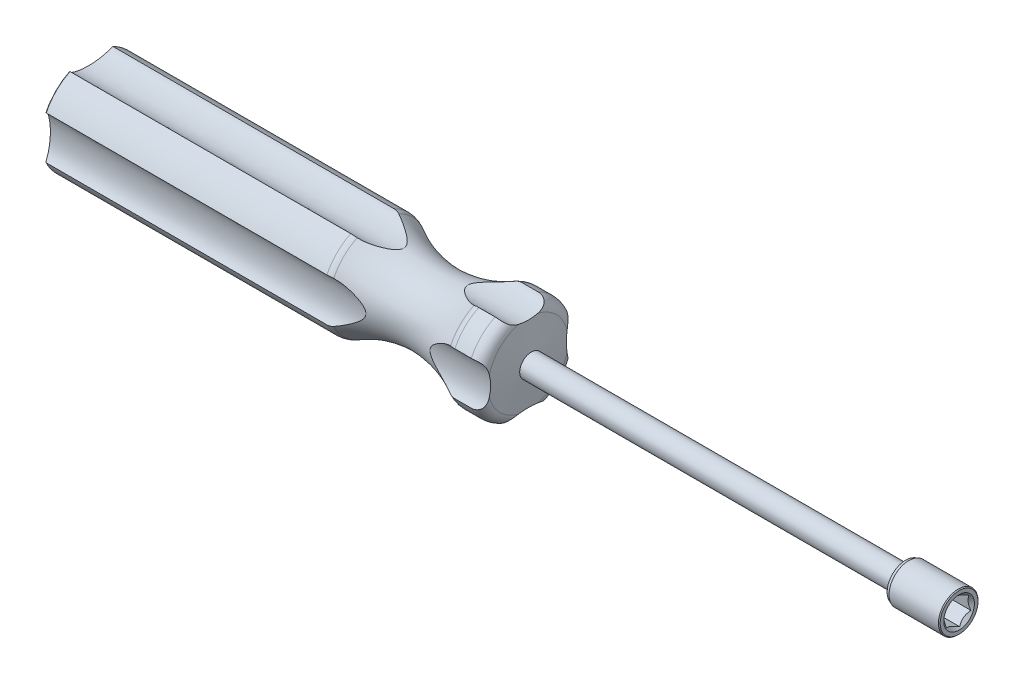
SolidWorks part; units mm, degrees
ref_plane "Front Plane" through (0, 0, 0) normal (0, 0, 1) x (1, 0, 0)
ref_plane "Top Plane" through (0, 0, 0) normal (0, 1, 0) x (1, 0, 0)
ref_plane "Right Plane" through (0, 0, 0) normal (1, 0, 0) x (0, 0, -1)
sketch "Sketch1" plane through (0, 0, 0) normal (0, 0, 1) x (1, 0, 0)
  line L0 (0, 0) -> (113.716, 0)
  line L1 (0, 4) -> (113.716, 4)
  line L4 (121.1868, 0) -> (113.716, 0)
  line L5 (113.716, 4) -> (114.9014, 6.8393)
  line L6 (0, 4) -> (-66.9286, 4)
  line L7 (114.9014, 6.8393) -> (133.21, 6.8393)
  line L8 (0, 0) -> (-66.9286, 0)
  line L9 (-66.9286, 4) -> (-66.9286, 0)
  line L10 (133.21, 6.8393) -> (133.21, 0)
  line L11 (133.21, 0) -> (121.1868, 0)
  dimension "D1" = 4
revolve "Revolve1" add sketch "Sketch1" angle 360 about L8
sketch "Sketch6" plane through (133.21, 0, 0) normal (1, 0, 0) x (0, 0, -1)
  line L1 (3.8609, 2.9631) -> (-0.6356, 4.8252)
  line L2 (-0.6356, 4.8252) -> (-4.4966, 1.8621)
  line L3 (-4.4966, 1.8621) -> (-3.8609, -2.9631)
  line L4 (-3.8609, -2.9631) -> (0.6356, -4.8252)
  line L5 (0.6356, -4.8252) -> (4.4966, -1.8621)
  line L6 (4.4966, -1.8621) -> (3.8609, 2.9631)
  circle A0 centre (0, 0) radius 4.2148 construction
extrude "Cut-Extrude4" cut sketch "Sketch6" against normal blind 14
sketch "Sketch7" plane through (133.21, 0, 0) normal (1, 0, 0) x (0, 0, -1)
  circle A0 centre (0, 0) radius 5.3031
extrude "Cut-Extrude5" cut sketch "Sketch7" against normal blind 14 draft 46
sketch "Sketch5" plane through (-66.9286, 0, 0) normal (-1, 0, 0) x (0, 0, 1)
  circle A0 centre (-3.5737, -1.7969) radius 0.5392
  circle A1 centre (0, 0) radius 4 construction
  circle A2 centre (-3.343, 2.1964) radius 0.5392
  circle A3 centre (0.2306, 3.9933) radius 0.5392
  circle A4 centre (3.5737, 1.7969) radius 0.5392
  circle A5 centre (3.343, -2.1964) radius 0.5392
  circle A6 centre (-0.2306, -3.9933) radius 0.5392
  point P16 (0, 0)
  dimension "D1" = 6
extrude "Cut-Extrude3" cut sketch "Sketch5" against normal blind 24
sketch "Sketch3" plane through (0, 0, 0) normal (0, 0, 1) x (1, 0, 0)
  line L0 (-14.7049, 4) -> (-66.9286, 4)
  line L1 (113.716, 4) -> (-42.9286, 4) construction
  line L2 (-66.9286, 4) -> (-66.9286, 0)
  line L3 (-66.9286, 4) -> (-66.9286, -4) construction
  line L4 (-66.9286, 0) -> (-168.5108, 0)
  line L6 (-166.6614, 17.4031) -> (-68.59, 17.4031)
  line L7 (-16.1421, 17.4031) -> (-14.7049, 4)
  line L10 (-26.4143, 17.4031) -> (-16.1421, 17.4031)
  ellipse E0 centre (-166.6614, 0) end of major axis (-166.6614, 17.4031) minor radius 1.8494 (-166.6614, 17.4031) -> (-168.5108, 0) ccw
  spline S0 degree 3 poles (-68.59, 17.4031) (-62.8793, 14.1005) (-49.0363, 9.4869) (-34.8234, 12.7895) (-26.4143, 17.4031) knots 0.086154 0.086154 0.086154 0.086154 0.431459 0.913846 0.913846 0.913846 0.913846
revolve "Revolve2" add sketch "Sketch3" angle 360 about L4
fillet "Fillet1" radius 4 3 edges at (-16.1421, 0, -17.4031) (-26.4143, 0, -17.4031) (-68.59, 0, -17.4031)
sketch "Sketch4" plane through (0, 0, 0) normal (1, 0, 0) x (0, 0, -1)
  ellipse E0 centre (0, 16.4526) end of major axis (7.658, 16.4526) minor radius 3.3504
extrude "Cut-Extrude2" cut sketch "Sketch4" against normal blind 175
pattern_circular "CirPattern2" count 4 over 360 about axis through (-14.7049, 0, 0) along (1, 0, 0) of "Cut-Extrude2"
chamfer "Chamfer1" distance 0.5 angle 45 2 edges at (113.716, 0, -4) (114.9014, 0, -6.8393)
chamfer "Chamfer2" distance 0.3 angle 45 1 edges at (133.21, 0, -6.8393)
